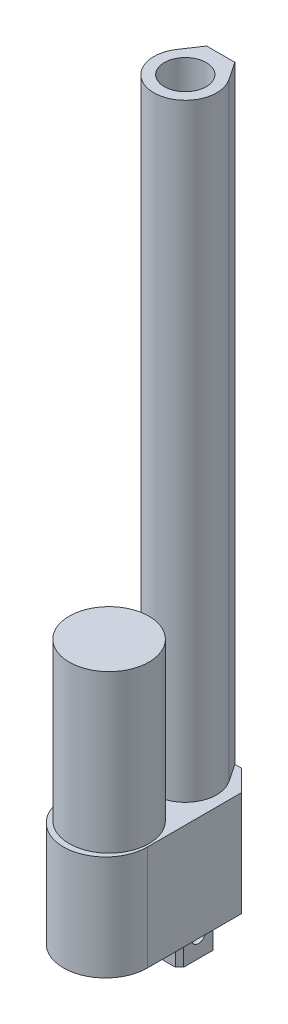
SolidWorks part; units mm, degrees
ref_plane "前视基准面" through (0, 0, 0) normal (0, 0, 1) x (1, 0, 0)
ref_plane "上视基准面" through (0, 0, 0) normal (0, 1, 0) x (1, 0, 0)
ref_plane "右视基准面" through (0, 0, 0) normal (1, 0, 0) x (0, 0, -1)
sketch "草图1" plane through (0, 0, 0) normal (0, 1, 0) x (1, 0, 0)
  line L1 (-20, 27.5) -> (20, 27.5)
  line L2 (-20, 27.5) -> (-20, -27.5)
  line L4 (20, 27.5) -> (20, -27.5)
  line L5 (-20, 27.5) -> (20, -27.5) construction
  line L6 (-20, -27.5) -> (20, 27.5) construction
  arc A0 (-20, -27.5) -> (20, -27.5) centre (0, -27.5) ccw
  point P0 (0, 0)
  dimension "D1" = 40
  dimension "D2" = 55
extrude "凸台-拉伸1" add sketch "草图1" along normal blind 50
sketch "草图2" plane through (0, 50, 0) normal (0, 1, 0) x (1, 0, 0)
  circle A0 centre (0, -25.7726) radius 19
  dimension "D1" = 38
extrude "凸台-拉伸2" add sketch "草图2" along normal blind 75
sketch "草图3" plane through (0, 50, 0) normal (0, 1, 0) x (1, 0, 0)
  line L0 (-13.8845, 18.7552) -> (-12.5776, 18.7552) construction
  line L1 (0, 42.5034) -> (0, 6.1961) construction
  line L2 (-12.4733, 18.9135) -> (-6.7378, 27.5)
  line L3 (20, 27.5) -> (-20, 27.5) construction
  line L4 (12.4733, 18.9135) -> (6.7378, 27.5)
  line L5 (-6.7378, 27.5) -> (6.7378, 27.5)
  line L6 (12.5776, 18.7552) -> (14.0408, 18.7552) construction
  arc A0 (-12.4733, 18.9135) -> (12.4733, 18.9135) centre (0, 10.5818) ccw
  dimension "D1" = 30
extrude "凸台-拉伸3" add sketch "草图3" along normal blind 290
sketch "草图4" plane through (0, 340, 0) normal (0, 1, 0) x (1, 0, 0)
  circle A0 centre (0, 10.5818) radius 10
  dimension "D1" = 20
extrude "切除-拉伸1" cut sketch "草图4" against normal blind 170
sketch "草图5" plane through (0, 0, 0) normal (0, -1, 0) x (1, 0, 0)
  line L0 (20, -27.5) -> (-20, -27.5) construction
  line L1 (-8.6674, 1.5) -> (9.3326, 1.5)
  line L2 (-8.6674, 1.5) -> (-8.6674, -16.5)
  line L3 (-8.6674, -16.5) -> (9.3326, -16.5)
  line L4 (9.3326, 1.5) -> (9.3326, -16.5)
  line L5 (-8.6674, 1.5) -> (9.3326, -16.5) construction
  line L6 (-8.6674, -16.5) -> (9.3326, 1.5) construction
  point P0 (0.3326, -7.5)
  dimension "D1" = 18
  dimension "D2" = 18
  dimension "D3" = 20
extrude "凸台-拉伸4" add sketch "草图5" along normal blind 19
sketch "草图7" plane through (9.3326, 0, 0) normal (1, 0, 0) x (0, 0, -1)
  line L0 (16.5, -19) -> (-1.5, -19) construction
  circle A0 centre (7.5, -9.5) radius 3.25
  dimension "D1" = 9.5
  dimension "D2" = 6.5
extrude "切除-拉伸2" cut sketch "草图7" against normal blind 19
chamfer "倒角1" distance 10 angle 45 2 edges at (20, 25, -27.5) (-20, 25, -27.5)
chamfer "倒角2" distance 2 angle 45 4 edges at (-8.6674, -9.5, 1.5) (9.3326, -9.5, 1.5) (9.3326, -9.5, -16.5) (-8.6674, -9.5, -16.5)
